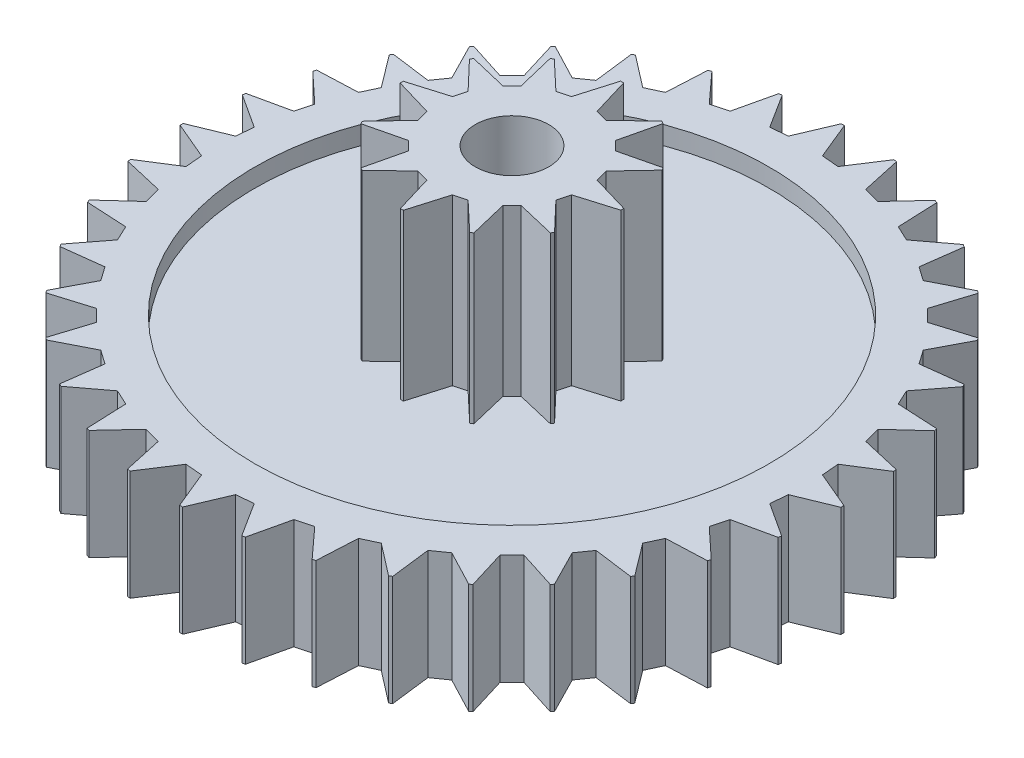
SolidWorks part; units mm, degrees
ref_plane "Front Plane" through (0, 0, 0) normal (0, 0, 1) x (1, 0, 0)
ref_plane "Top Plane" through (0, 0, 0) normal (0, 1, 0) x (1, 0, 0)
ref_plane "Right Plane" through (0, 0, 0) normal (1, 0, 0) x (0, 0, -1)
sketch "Sketch2" plane through (0, 0, 0) normal (0, 1, 0) x (1, 0, 0)
  circle A0 centre (0, 0) radius 4.5
extrude "Boss-Extrude1" add sketch "Sketch2" along normal blind 1.5
sketch "Sketch3" plane through (0, 1.5, 0) normal (0, 1, 0) x (1, 0, 0)
  line L0 (0, 0) -> (0, 5.8828) construction
  line L1 (0, 0) -> (0.4167, 7.1541) construction
  line L2 (0, 0) -> (0.6915, 5.9163) construction
  line L3 (0, 0) -> (1.1608, 6.5832) construction
  circle A0 centre (0, 0) radius 4
  dimension "D1" = 3.333
  dimension "D2" = 3.333
  dimension "D3" = 3.333
sketch "Sketch4" plane through (0, 1.5, 0) normal (0, 1, 0) x (1, 0, 0)
  line L0 (0.2326, 3.9932) -> (0, 4.5588)
  line L1 (0, 0) -> (0.4167, 7.1541) construction
  line L2 (0, 0) -> (0, 5.8828) construction
  line L3 (0, 4.5588) -> (0.7885, 4.4718)
  line L4 (0, 0) -> (1.1608, 6.5832) construction
  line L5 (0.7885, 4.4718) -> (0.4644, 3.973)
  line L6 (0, 0) -> (0.6915, 5.9163) construction
  line L7 (0.4644, 3.973) -> (0.2326, 3.9932)
  circle A0 centre (0, 0) radius 4 construction
extrude "Cut-Extrude1" cut sketch "Sketch4" against normal through all
sketch "Sketch5" plane through (0, 0, 0) normal (1, 0, 0) x (0, 0, -1)
  line L0 (0, 0) -> (0, 2.2331) construction
pattern_circular "CirPattern1" count 36 every 10 about axis through (0, 0, 0) along (0, 1, 0) of "Cut-Extrude1"
sketch "Sketch6" plane through (0, 1.5, 0) normal (0, 1, 0) x (1, 0, 0)
  circle A0 centre (0, 0) radius 3.5
extrude "Cut-Extrude2" cut sketch "Sketch6" against normal blind 0.25
sketch "Sketch7" plane through (0, 1.5, 0) normal (0, 1, 0) x (1, 0, 0)
  circle A0 centre (0, 0) radius 0.5
extrude "Cut-Extrude3" cut sketch "Sketch7" against normal through all
sketch "Sketch8" plane through (0, 0, 0) normal (0, -1, 0) x (-1, 0, 0)
  circle A0 centre (0, 0) radius 3.5
  circle A1 centre (0, 0) radius 1
extrude "Cut-Extrude4" cut sketch "Sketch8" against normal blind 0.25
sketch "Sketch9" plane through (0, 1.25, 0) normal (0, 1, 0) x (1, 0, 0)
  circle A0 centre (0, 0) radius 1.5
extrude "Boss-Extrude2" add sketch "Sketch9" along normal blind 2.25
sketch "Sketch10" plane through (0, 3.5, 0) normal (0, 1, 0) x (1, 0, 0)
  circle A0 centre (0, 0) radius 0.5
extrude "Cut-Extrude5" cut sketch "Sketch10" against normal through all
sketch "Sketch11" plane through (0, 3.5, 0) normal (0, 1, 0) x (1, 0, 0)
  line L0 (0, 0) -> (-2.1437, 0) construction
  line L1 (0, 0) -> (-2.1634, 0.3815) construction
  line L2 (0, 0) -> (-2.029, 0.7385) construction
  line L3 (0, 0) -> (-1.7892, 1.033) construction
  line L4 (-0.9848, 0.1736) -> (-1.5653, 0)
  line L5 (-1.5653, 0) -> (-1.3636, 0.7873)
  line L6 (-1.3636, 0.7873) -> (-0.9397, 0.342)
  line L7 (-0.9848, 0.1736) -> (-0.9397, 0.342)
  circle A0 centre (0, 0) radius 1
  dimension "D1" = 10
  dimension "D2" = 10
  dimension "D3" = 10
extrude "Cut-Extrude6" cut sketch "Sketch11" against normal blind 2.25 contours L4 L5 L6 L7
pattern_circular "CirPattern2" count 12 every 30 about axis through (0, 0, 0) along (0, 1, 0) of "Cut-Extrude6"
